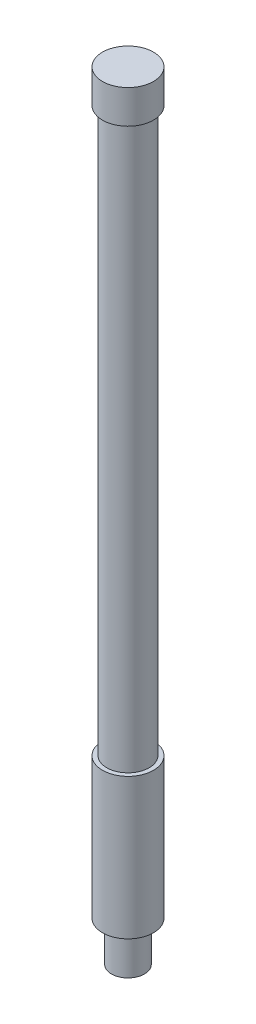
SolidWorks part; units mm, degrees
material "6061 Alloy"
ref_plane "Front Plane" through (0, 0, 0) normal (0, 0, 1) x (1, 0, 0)
ref_plane "Top Plane" through (0, 0, 0) normal (0, 1, 0) x (1, 0, 0)
ref_plane "Right Plane" through (0, 0, 0) normal (1, 0, 0) x (0, 0, -1)
sketch "Sketch1" plane through (0, 0, 0) normal (0, 0, 1) x (1, 0, 0)
  line L0 (0, 349.25) -> (0, 0) construction
  line L1 (0, 0) -> (0, -19.05) construction
  line L2 (0, -19.05) -> (7.8105, -19.05)
  line L3 (7.8105, -19.05) -> (7.8105, 0)
  line L4 (7.8105, 0) -> (12.065, 0)
  line L5 (12.065, 0) -> (12.065, 66.675)
  line L6 (12.065, 66.675) -> (10.033, 66.675)
  line L7 (10.033, 66.675) -> (10.033, 333.375)
  line L8 (10.033, 333.375) -> (12.065, 333.375)
  line L9 (12.065, 333.375) -> (12.065, 349.25)
  line L10 (12.065, 349.25) -> (0, 349.25)
  line L11 (0, 349.25) -> (0, -19.05)
  dimension "D1" = 20.066
  dimension "D2" = 24.13
  dimension "D3" = 24.13
  dimension "D4" = 15.621
  dimension "D5" = 19.05
  dimension "D6" = 66.675
  dimension "D7" = 15.875
  dimension "D8" = 266.7
revolve "Revolve1" add sketch "Sketch1" angle 360 about L11
